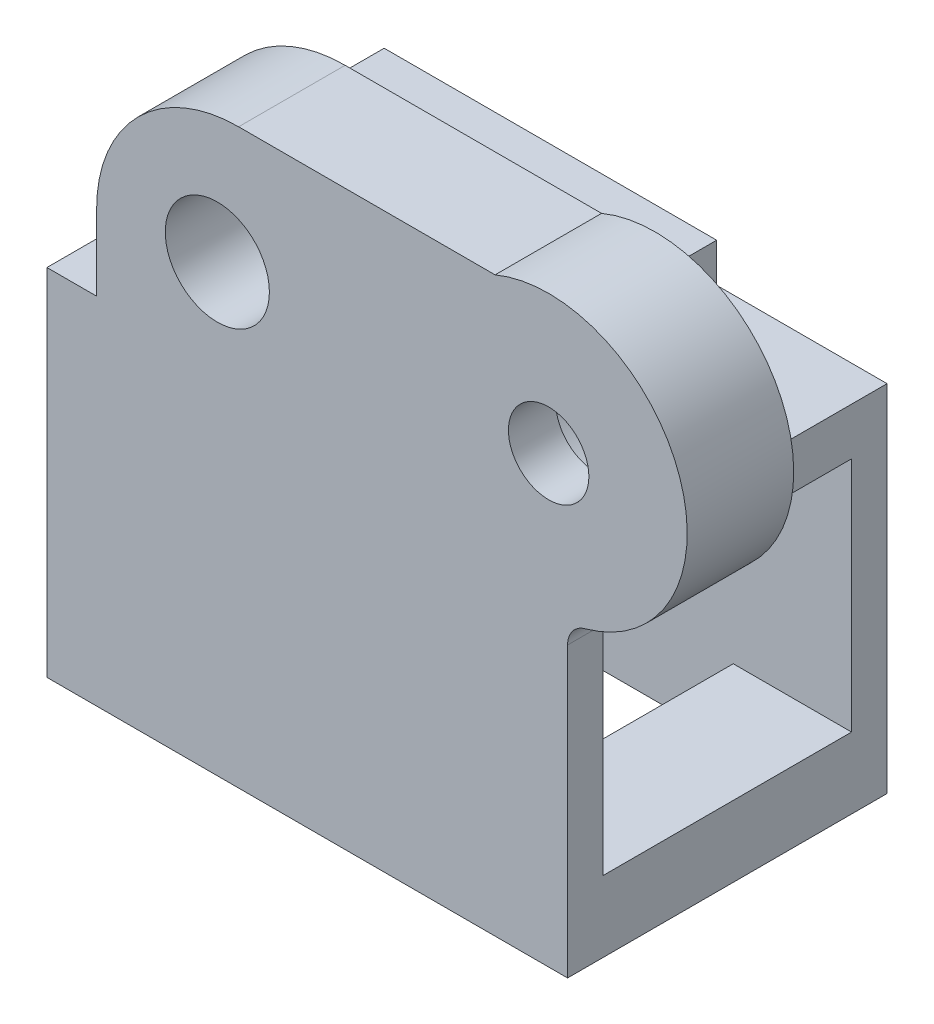
SolidWorks part; units mm, degrees
ref_plane "Front Plane" through (0, 0, 0) normal (0, 0, 1) x (1, 0, 0)
ref_plane "Top Plane" through (0, 0, 0) normal (0, 1, 0) x (1, 0, 0)
ref_plane "Right Plane" through (0, 0, 0) normal (1, 0, 0) x (0, 0, -1)
sketch "Sketch1" plane through (0, 0, 0) normal (0, 1, 0) x (1, 0, 0)
  line L0 (4.75, 6.7) -> (16.75, 6.7) construction
  line L1 (0, 0) -> (21.5, 0)
  line L2 (0, 0) -> (0, 10.5)
  line L3 (0, 10.5) -> (21.5, 10.5)
  line L4 (21.5, 0) -> (21.5, 10.5)
  line L5 (0.75, 6.7) -> (4.1778, 6.7) construction
  point P13 (10.75, 6.7)
  point P14 (10.75, 10.5)
  dimension "D1" = 10.5
  dimension "D7" = 21.5
extrude "Boss-Extrude1" add sketch "Sketch1" along normal blind 2
sketch "Sketch10" plane through (0, 0, 0) normal (0, -1, 0) x (1, 0, 0)
  line L0 (5.75, -5.25) -> (15.75, -5.25) construction
  line L2 (0.75, -0.25) -> (20.75, -0.25)
  line L3 (0.75, -0.25) -> (0.75, -10.25)
  line L4 (0.75, -10.25) -> (20.75, -10.25)
  line L5 (20.75, -0.25) -> (20.75, -10.25)
  line L6 (21.5, -10.5) -> (0, -10.5) construction
  line L7 (0, -10.5) -> (0, 0) construction
  circle A0 centre (5.75, -5.25) radius 4
  circle A1 centre (15.75, -5.25) radius 1.5
  point P9 (10.75, -10.5)
  point P10 (0, -5.25)
  point P11 (10.75, -5.25)
  point P12 (10.75, -0.25)
  point P14 (10.75, -10.25)
  point P17 (0.75, -5.25)
  dimension "D2" = 3
  dimension "D5" = 8
  dimension "D1" = 10
  dimension "D3" = 10
  dimension "D4" = 20
sketch "Sketch3" plane through (0, 2, 0) normal (0, 1, 0) x (1, 0, 0)
  line L0 (0, 10.5) -> (-1, 10.5)
  line L1 (0, 10.5) -> (21.5, 10.5)
  line L2 (0, 10.5) -> (0, 0)
  line L3 (0, 0) -> (21.5, 0)
  line L4 (21.5, 10.5) -> (21.5, 0)
  line L5 (-1, 12) -> (22.5, 12)
  line L6 (-1, 12) -> (-1, -1.5)
  line L7 (-1, -1.5) -> (22.5, -1.5)
  line L8 (22.5, 12) -> (22.5, -1.5)
  line L9 (0, 0) -> (-1, 0)
  line L10 (21.5, 10.5) -> (22.5, 10.5)
  line L11 (21.5, 0) -> (22.5, 0)
  line L12 (0, 10.5) -> (0, 12)
  line L13 (0, 0) -> (0, -1.5)
  line L14 (21.5, -1.5) -> (21.5, 12)
  point P10 (21.5, 5.25)
  line M8 (0, 10.5) -> (0, 0)
  line M9 (0, 0) -> (21.5, 0)
  line M11 (21.5, 10.5) -> (0, 10.5)
  dimension "D1" = 1
  dimension "D2" = 1.5
  dimension "D3" = 1
  dimension "D4" = 1.5
extrude "Boss-Extrude3" add sketch "Sketch3" against normal blind 15 contours L10 L8 L5 L6 L0 M11 | L11 L9 L6 L7 L8 M9 | L7 L14 L13 M9 | L13 L9 L6 L7 | L9 L0 L6 M8 | L0 L12 L5 L6 | L14 L5 L12 M11
sketch "Sketch8" plane through (0, 0, 0) normal (0, 0, -1) x (-1, 0, 0)
  line L1 (-22.5, 2) -> (-21.5, 2)
  line L2 (-22.5, 2) -> (-22.5, 0)
  line L3 (-22.5, 0) -> (-21.5, 0)
  line L4 (-21.5, 2) -> (-21.5, 0)
extrude "Boss-Extrude7" add sketch "Sketch8" along normal up to next
sketch "Sketch5" plane through (0, -13, 0) normal (0, -1, 0) x (1, 0, 0)
  line L0 (17.5, 0) -> (17.5, -10.5)
  line L1 (0, 0) -> (22.5, 0) construction
  line L2 (0, -10.5) -> (22.5, -10.5) construction
  line L3 (17.5, -10.5) -> (22.5, -10.5)
  line L4 (22.5, -10.5) -> (22.5, 1.5)
  line L5 (22.5, 1.5) -> (17.5, 1.5)
  line L6 (-1, 1.5) -> (22.5, 1.5) construction
  line L7 (17.5, 1.5) -> (17.5, 0)
  dimension "D1" = 5
extrude "Boss-Extrude5" add sketch "Sketch5" against normal blind 3
sketch "Sketch6" plane through (0, 0, 1.5) normal (0, 0, 1) x (1, 0, 0)
  line L9 (-1, -5.5) -> (15.2709, -5.5) construction
  line L10 (-1, 2) -> (22.5, 2) construction
  line L16 (22.5, -13) -> (22.5, 2) construction
  line L17 (22.5, 2) -> (22.5, 5.8) construction
  line L18 (22.5, 5.8) -> (21.7, 5.8) construction
  line L19 (0, 0) -> (22.5, 0) construction
  line L20 (22.5, 0) -> (22.5, 2)
  line L21 (22.5, 2) -> (17.2458, 2)
  circle A0 centre (21.7, 5.8) radius 1.7
  arc A1 (17.2458, 2) -> (22.5, 0) centre (21.7, 5.8) cw
  dimension "D1" = 3.4
  dimension "D3" = 3.8
  dimension "D4" = 0.8
extrude "Boss-Extrude6" add sketch "Sketch6" against normal blind 2 separate body
sketch "Sketch9" plane through (0, 0, -0.5) normal (0, 0, -1) x (-1, 0, 0)
  line L1 (1, 2) -> (-22.5, 2) construction
  line L2 (-22.5775, 2) -> (-17.2458, 2)
  arc A0 (-22.5, 0) -> (-17.2458, 2) centre (-21.7, 5.8) cw
  arc A1 (-17.2458, 2) -> (-22.5, 0) centre (-21.7, 5.8) ccw construction
  arc A2 (-22.5775, 2) -> (-20.8225, 2) centre (-21.7, 5.8) cw
  arc M2 (-17.2458, 2) -> (-22.5, 0) centre (-21.7, 5.8) ccw
  line M3 (-22.5, 0) -> (-22.5, 2)
  dimension "D1" = 3.9
extrude "Boss-Extrude8" add sketch "Sketch9" along normal blind 2.5 contours L2 A2 M2 M3
fillet "Fillet1" radius 1 2 edges at (17.2458, 2, -0.75) (22.5, 0, 0.75)
sketch "Sketch12" plane through (0, -13, 0) normal (0, -1, 0) x (1, 0, 0)
  line L0 (-1, -12) -> (-1, 1.5) construction
  line L1 (0, 0) -> (-1, 0)
  line L2 (0, 0) -> (0, -10.5)
  line L3 (0, -10.5) -> (-1, -10.5)
  line L4 (-1, 0) -> (-1, -10.5)
  line L5 (0, -10.5) -> (17.5, -10.5) construction
extrude "Cut-Extrude1" cut sketch "Sketch12" against normal up to surface (13 mm away) up to face at (13.5, 0, -4.8)
sketch "Sketch13" plane through (-1, 0, 0) normal (-1, 0, 0) x (0, 0, 1)
  line L0 (-12, -13) -> (-12, 2)
  line L1 (-12, 2) -> (1.5, 2)
  line L2 (1.5, 2) -> (1.5, -13)
  line L3 (1.5, -13) -> (0, -13)
  line L4 (0, -13) -> (0, 0)
  line L5 (0, 0) -> (-10.5, 0)
  line L6 (-10.5, 0) -> (-10.5, -13)
  line L7 (-10.5, -13) -> (-12, -13)
extrude "Cut-Extrude2" cut sketch "Sketch13" against normal blind 1.5
sketch "Sketch15" plane through (0, 2, 0) normal (0, 1, 0) x (1, 0, 0)
  line L0 (5.75, 5.25) -> (15.75, 5.25) construction
  line L1 (5.85, -0.15) -> (16.65, -0.15) construction
  line L2 (5.85, -0.15) -> (5.85, 10.65) construction
  line L3 (5.85, 10.65) -> (16.65, 10.65)
  line L4 (16.65, -0.15) -> (16.65, 10.65)
  line L5 (5.85, -0.15) -> (16.65, 10.65) construction
  line L6 (5.85, 10.65) -> (16.65, -0.15) construction
  line L7 (5.85, 10.65) -> (2.6, 10.65)
  line L8 (2.6, 10.65) -> (2.6, -1.5)
  line L10 (0.5, -1.5) -> (15.443, -1.5) construction
  line L11 (2.6, -1.5) -> (16.65, -1.5)
  line L12 (16.65, -1.5) -> (16.65, -0.15)
  circle A0 centre (11.25, 5.25) radius 2.2
  point P0 (11.25, 5.25)
  point P10 (9.05, 5.25)
  point P11 (11.25, 7.45)
  dimension "D2" = 4.4
  dimension "D1" = 4.5
  dimension "D3" = 3.2
  dimension "D4" = 3.2
  dimension "D5" = 3.25
extrude "Boss-Extrude9" add sketch "Sketch15" along normal blind 3
sketch "Sketch16" plane through (0, 0, 1.5) normal (0, 0, 1) x (1, 0, 0)
  line L0 (2.6, 5) -> (2.6, 11.2)
  line L1 (2.6, 11.2) -> (19.4373, 11.2)
  line L2 (2.6, 5) -> (15.9, 5)
  arc A0 (23.2374, 0.1505) -> (15.9, 5) centre (21.7, 5.8) ccw construction
  arc A1 (19.4373, 11.2) -> (15.9, 5) centre (21.7, 5.8) ccw
  circle A2 centre (7.7, 5.8) radius 0.6702
  point P0 (7.7, 5.8)
  point P1 (21.7, 5.8)
  dimension "D1" = 14
  dimension "D2" = 5.4
extrude "Boss-Extrude10" add sketch "Sketch16" against normal blind 4.5
sketch "Sketch17" plane through (0, 0, 1.5) normal (0, 0, 1) x (1, 0, 0)
  circle A0 centre (7.7, 5.8) radius 2.2
  dimension "D1" = 4.4
extrude "Cut-Extrude3" cut sketch "Sketch17" against normal blind 4.5
sketch "Sketch18" plane through (0, 2, 0) normal (0, 1, 0) x (1, 0, 0)
  circle A0 centre (11.25, 5.25) radius 2.2
extrude "Cut-Extrude4" cut sketch "Sketch18" against normal blind 4.5
fillet "Fillet2" radius 6 1 edges at (2.6, 11.2, -0.75)
